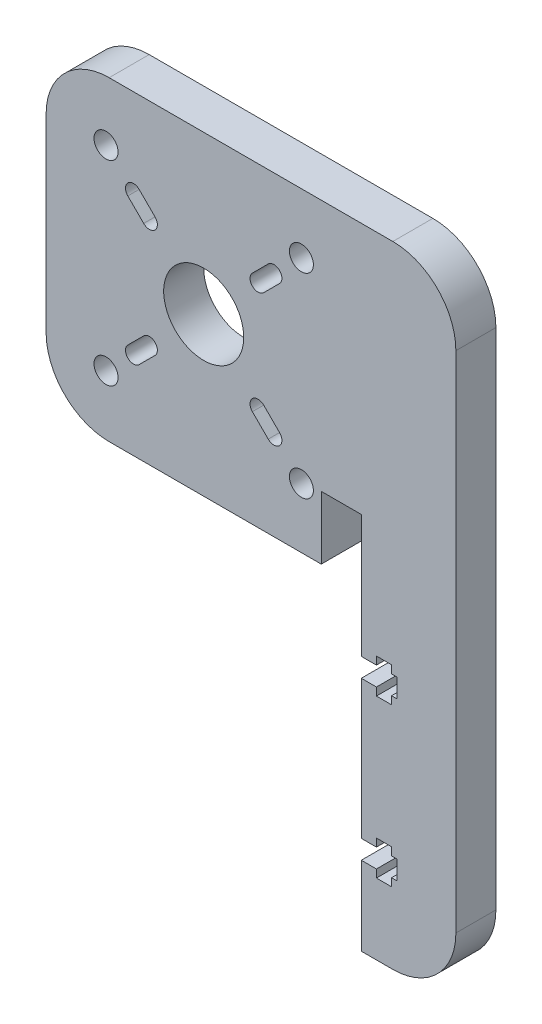
SolidWorks part; units mm, degrees
ref_plane "Front Plane" through (0, 0, 0) normal (0, 0, 1) x (1, 0, 0)
ref_plane "Top Plane" through (0, 0, 0) normal (0, 1, 0) x (1, 0, 0)
ref_plane "Right Plane" through (0, 0, 0) normal (1, 0, 0) x (0, 0, -1)
sketch "Sketch1" plane through (0, 0, 0) normal (0, 0, 1) x (1, 0, 0)
  line L0 (-11.1355, 11.1355) -> (-8.621, 8.621) construction
  line L1 (-10.2375, 12.0335) -> (-7.723, 9.5191)
  line L2 (-12.0335, 10.2375) -> (-9.5191, 7.723)
  line L3 (-6.35, 0) -> (6.35, 0) construction
  line L4 (-8.621, 8.621) -> (0, 0) construction
  line L5 (-15.494, 15.494) -> (-10.9972, 10.9972) construction
  line L6 (15.494, 15.494) -> (10.9972, 10.9972) construction
  line L7 (8.621, 8.621) -> (0, 0) construction
  line L8 (11.1355, 11.1355) -> (8.621, 8.621) construction
  line L9 (12.0335, 10.2375) -> (9.5191, 7.723)
  line L10 (10.2375, 12.0335) -> (7.723, 9.5191)
  line L11 (15.494, -15.494) -> (10.9972, -10.9972) construction
  line L12 (8.621, -8.621) -> (0, 0) construction
  line L13 (11.1355, -11.1355) -> (8.621, -8.621) construction
  line L14 (10.2375, -12.0335) -> (7.723, -9.5191)
  line L15 (12.0335, -10.2375) -> (9.5191, -7.723)
  line L16 (-15.494, -15.494) -> (-10.9972, -10.9972) construction
  line L17 (-8.621, -8.621) -> (0, 0) construction
  line L18 (-11.1355, -11.1355) -> (-8.621, -8.621) construction
  line L19 (-12.0335, -10.2375) -> (-9.5191, -7.723)
  line L20 (-10.2375, -12.0335) -> (-7.723, -9.5191)
  line L21 (25, 25) -> (40, 25)
  line L22 (-25, 25) -> (25, 25)
  line L23 (-25, 25) -> (-25, -25)
  line L24 (-25, -25) -> (25, -25)
  line L25 (25, 25) -> (25, -25)
  line L26 (40, 25) -> (40, -75)
  line L27 (40, -75) -> (25, -75)
  line L28 (25, -75) -> (25, -25)
  line L29 (25, -34.5) -> (27.4, -34.5)
  line L30 (27.4, -34.5) -> (27.4, -33.25)
  line L31 (27.4, -33.25) -> (29.8, -33.25)
  line L32 (29.8, -33.25) -> (29.8, -34.5)
  line L33 (29.8, -34.5) -> (30.65, -34.5)
  line L34 (30.65, -34.5) -> (30.65, -37.5)
  line L35 (30.65, -37.5) -> (29.8, -37.5)
  line L36 (29.8, -37.5) -> (29.8, -38.75)
  line L37 (29.8, -38.75) -> (27.4, -38.75)
  line L38 (27.4, -38.75) -> (27.4, -37.5)
  line L39 (27.4, -37.5) -> (25, -37.5)
  line L40 (18.65, -25) -> (18.65, -15)
  line L41 (18.65, -15) -> (25, -15)
  line L42 (25, -59.5) -> (27.4, -59.5)
  line L43 (27.4, -59.5) -> (27.4, -58.25)
  line L44 (27.4, -58.25) -> (29.8, -58.25)
  line L45 (29.8, -58.25) -> (29.8, -59.5)
  line L46 (29.8, -59.5) -> (30.65, -59.5)
  line L47 (30.65, -59.5) -> (30.65, -62.5)
  line L48 (30.65, -62.5) -> (29.8, -62.5)
  line L49 (29.8, -63.75) -> (27.4, -63.75)
  line L50 (29.8, -62.5) -> (29.8, -63.75)
  line L51 (27.4, -63.75) -> (27.4, -62.5)
  line L52 (27.4, -62.5) -> (25, -62.5)
  circle A0 centre (0, 0) radius 6.35
  arc A1 (-10.2375, 12.0335) -> (-12.0335, 10.2375) centre (-11.1355, 11.1355) ccw
  arc A2 (-9.5191, 7.723) -> (-7.723, 9.5191) centre (-8.621, 8.621) ccw
  circle A3 centre (-15.494, 15.494) radius 1.905
  circle A4 centre (15.494, 15.494) radius 1.905
  arc A5 (12.0335, 10.2375) -> (10.2375, 12.0335) centre (11.1355, 11.1355) ccw
  arc A6 (7.723, 9.5191) -> (9.5191, 7.723) centre (8.621, 8.621) ccw
  circle A7 centre (15.494, -15.494) radius 1.905
  arc A8 (10.2375, -12.0335) -> (12.0335, -10.2375) centre (11.1355, -11.1355) ccw
  arc A9 (9.5191, -7.723) -> (7.723, -9.5191) centre (8.621, -8.621) ccw
  circle A10 centre (-15.494, -15.494) radius 1.905
  arc A11 (-12.0335, -10.2375) -> (-10.2375, -12.0335) centre (-11.1355, -11.1355) ccw
  arc A12 (-7.723, -9.5191) -> (-9.5191, -7.723) centre (-8.621, -8.621) ccw
  point P5 (-9.8783, 9.8783)
  point P21 (9.8783, 9.8783)
  point P32 (9.8783, -9.8783)
  point P43 (-9.8783, -9.8783)
  point P52 (0, 0)
  point P78 (30.65, -36)
  dimension "D1" = 12.7
  dimension "D3" = 1.27
  dimension "D6" = 3.81
  dimension "D2" = 1.778
  dimension "D4" = 45
  dimension "D5" = 13.97
  dimension "D7" = 15.494
  dimension "D9" = 25
  dimension "D10" = 50
  dimension "D11" = 25
  dimension "D12" = 50
  dimension "D13" = 3
  dimension "D14" = 5.65
  dimension "D15" = 5.5
  dimension "D16" = 2.4
  dimension "D17" = 2.75
  dimension "D18" = 2.4
  dimension "D19" = 15
  dimension "D20" = 100
  dimension "D21" = 37.5
  dimension "D22" = 6.35
  dimension "D23" = 10
  dimension "D24" = 2
  dimension "D8" = 4
extrude "Boss-Extrude1" add sketch "Sketch1" along normal blind 6.35
fillet "Fillet1" radius 10 4 edges at (40, -75, 3.175) (40, 25, 3.175) (-25, -25, 3.175) (-25, 25, 3.175)
